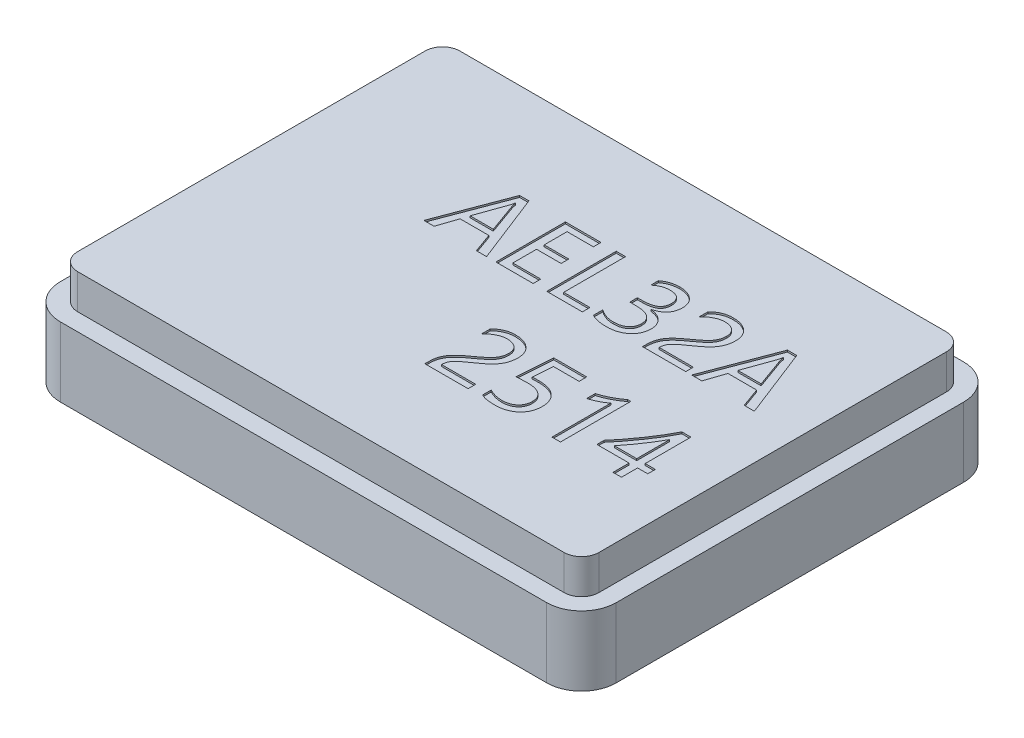
SolidWorks part; units mm, degrees
ref_plane "前视基准面" through (0, 0, 0) normal (0, 0, 1) x (1, 0, 0)
ref_plane "上视基准面" through (0, 0, 0) normal (0, 1, 0) x (1, 0, 0)
ref_plane "右视基准面" through (0, 0, 0) normal (1, 0, 0) x (0, 0, -1)
sketch "草图1" plane through (0, 0, 0) normal (0, 1, 0) x (1, 0, 0)
  line L1 (-1.6, -1.2) -> (1.6, -1.2)
  line L2 (-1.6, -1.2) -> (-1.6, 1.2)
  line L3 (-1.6, 1.2) -> (1.6, 1.2)
  line L4 (1.6, -1.2) -> (1.6, 1.2)
  line L5 (-1.6, -1.2) -> (1.6, 1.2) construction
  line L6 (-1.6, 1.2) -> (1.6, -1.2) construction
  point P0 (0, 0)
  dimension "D1" = 3.2
  dimension "D2" = 2.4
extrude "凸台-拉伸1" add sketch "草图1" along normal blind 0.4
fillet "圆角1" radius 0.2 4 edges at (-1.6, 0.2, -1.2) (1.6, 0.2, -1.2) (1.6, 0.2, 1.2) (-1.6, 0.2, 1.2)
sketch "草图2" plane through (0, 0.4, 0) normal (0, 1, 0) x (1, 0, 0)
  line L8 (1.4, 1.1) -> (-1.4, 1.1)
  line L9 (-1.5, 1) -> (-1.5, -1)
  line L10 (-1.4, -1.1) -> (1.4, -1.1)
  line L11 (1.5, -1) -> (1.5, 1)
  line L12 (1.4, 1.1) -> (-1.4, 1.1)
  line L13 (-1.5, 1) -> (-1.5, -1)
  line L14 (-1.4, -1.1) -> (1.4, -1.1)
  line L15 (1.5, -1) -> (1.5, 1)
  arc A8 (-1.4, 1.1) -> (-1.5, 1) centre (-1.4, 1) ccw
  arc A9 (-1.5, -1) -> (-1.4, -1.1) centre (-1.4, -1) ccw
  arc A10 (1.4, -1.1) -> (1.5, -1) centre (1.4, -1) ccw
  arc A11 (1.5, 1) -> (1.4, 1.1) centre (1.4, 1) ccw
  arc A12 (-1.4, 1.1) -> (-1.5, 1) centre (-1.4, 1) ccw
  arc A13 (-1.5, -1) -> (-1.4, -1.1) centre (-1.4, -1) ccw
  arc A14 (1.4, -1.1) -> (1.5, -1) centre (1.4, -1) ccw
  arc A15 (1.5, 1) -> (1.4, 1.1) centre (1.4, 1) ccw
  dimension "D1" = 0.1
extrude "凸台-拉伸2" add sketch "草图2" along normal blind 0.2 separate body
sketch "草图3" plane through (0, 0.6, 0) normal (0, 1, 0) x (1, 0, 0)
  text T0 "AEL32A\r\n" font "微软雅黑" height 0.4
  text T1 "2514" font "微软雅黑" height 0.4
  point P2 (-0.8686, -0.5919)
  point P3 (-0.664, 0.1518)
  point P4 (0, -0.743)
  point P5 (0, 0)
  point P6 (0, 0)
extrude "切除-拉伸1" cut sketch "草图3" against normal blind 0.01
